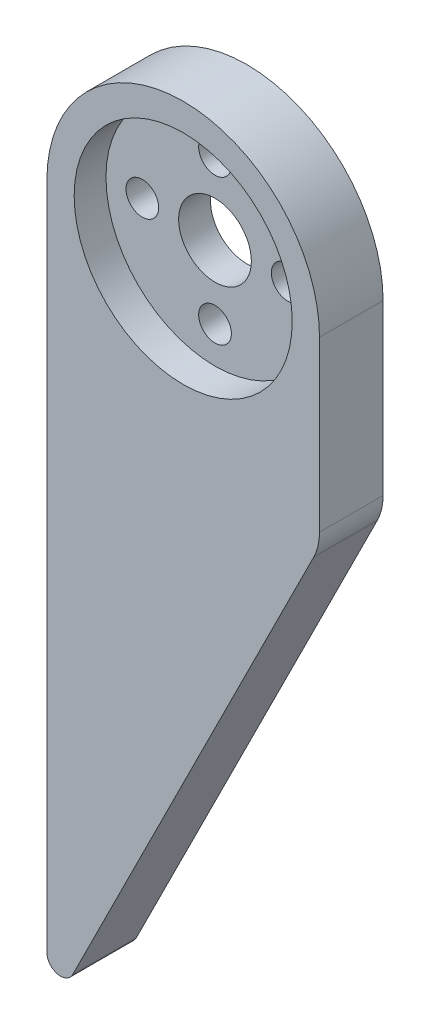
SolidWorks part; units mm, degrees
ref_plane "Plan de face" through (0, 0, 0) normal (0, 0, 1) x (1, 0, 0)
ref_plane "Plan de dessus" through (0, 0, 0) normal (0, 1, 0) x (1, 0, 0)
ref_plane "Plan de droite" through (0, 0, 0) normal (1, 0, 0) x (0, 0, -1)
sketch "Esquisse1" plane through (0, 0, 0) normal (0, 0, 1) x (1, 0, 0)
  line L0 (-15, 0) -> (-15, -80)
  line L1 (15, 0) -> (15, -20)
  line L2 (15, -20) -> (-15, -80)
  circle A0 centre (0, 0) radius 15
  circle A1 centre (0, 0) radius 4
  circle A2 centre (0, 0) radius 8 construction
  circle A3 centre (0, 8) radius 1.8
  circle A4 centre (8, 0) radius 1.8
  circle A5 centre (0, -8) radius 1.8
  circle A6 centre (-8, 0) radius 1.8
extrude "Boss.-Extru.1" add sketch "Esquisse1" along normal blind 7 contours A0 L0 L2 L1 | A0 A6 A5 A4 A3 A1
fillet "Congé1" radius 1.5 1 edges at (-15, -80, 3.5)
fillet "Congé2" radius 6 1 edges at (15, -20, 3.5)
sketch "Esquisse2" plane through (0, 0, 7) normal (0, 0, 1) x (1, 0, 0)
  circle A0 centre (0, 0) radius 12
extrude "Enlèv. mat.-Extru.1" cut sketch "Esquisse2" against normal blind 3.5
